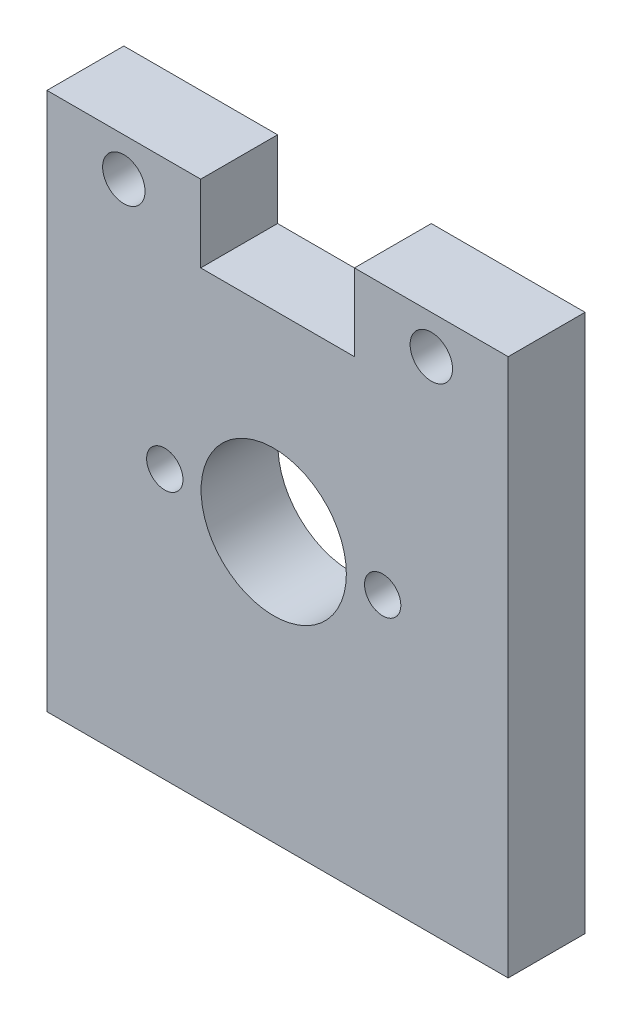
SolidWorks part; units mm, degrees
ref_plane "Front Plane" through (0, 0, 0) normal (0, 0, 1) x (1, 0, 0)
ref_plane "Top Plane" through (0, 0, 0) normal (0, 1, 0) x (1, 0, 0)
ref_plane "Right Plane" through (0, 0, 0) normal (1, 0, 0) x (0, 0, -1)
sketch "Sketch1" plane through (0, 0, 0) normal (0, 0, 1) x (1, 0, 0)
  line L1 (0, 0) -> (38.1, 0)
  line L2 (0, 0) -> (0, -44.45)
  line L3 (0, -44.45) -> (38.1, -44.45)
  line L4 (38.1, -44.45) -> (38.1, 0)
  dimension "D1" = 44.45
  dimension "D2" = 38.1
extrude "Boss-Extrude1" add sketch "Sketch1" along normal mid plane 6.35
sketch "Sketch2" [suppressed] plane through (0, 0, 3.175) normal (0, 0, 1) x (1, 0, 0)
  line L0 (6.2865, 0) -> (18.9865, 0)
  line L1 (6.2865, 0) -> (6.2865, -6.35)
  line L3 (18.9865, 0) -> (18.9865, -6.35)
  line L4 (76.2, -12.7) -> (76.2, 0) construction
  line L16 (76.2, 0) -> (0, 0) construction
  line L17 (14.1605, -13.97) -> (14.1605, -17.78)
  line L18 (16.4465, -13.97) -> (14.1605, -13.97)
  line L19 (16.4465, -11.43) -> (16.4465, -13.97)
  line L20 (14.1605, -11.43) -> (16.4465, -11.43)
  line L21 (11.1125, -13.97) -> (11.1125, -17.78)
  line L22 (8.8265, -13.97) -> (11.1125, -13.97)
  line L23 (8.8265, -11.43) -> (8.8265, -13.97)
  line L24 (11.1125, -11.43) -> (8.8265, -11.43)
  line L25 (11.1125, -6.35) -> (11.1125, -11.43)
  line L26 (14.1605, -17.78) -> (11.1125, -17.78)
  line L27 (14.1605, -6.35) -> (14.1605, -11.43)
  line L28 (14.1605, -6.35) -> (18.9865, -6.35)
  line L29 (6.2865, -6.35) -> (11.1125, -6.35)
  line L35 (12.6365, 0) -> (12.6365, -17.78) construction
  dimension "D1" = 12.7
  dimension "D2" = 6.35
  dimension "D3" = 11.43
  dimension "D4" = 13.97
  dimension "D5" = 17.78
  dimension "D6" = 3.048
  dimension "D7" = 3.048
  dimension "D8" = 7.62
  dimension "D9" = 3.81
  dimension "D10" = 1.524
  dimension "D11" = 65.0875
sketch "Sketch3" plane through (0, 0, 3.175) normal (0, 0, 1) x (1, 0, 0)
  line L1 (0, 0) -> (12.7, 0)
  line L2 (0, 0) -> (0, -12.7)
  line L3 (0, -12.7) -> (12.7, -12.7)
  line L4 (12.7, 0) -> (12.7, -12.7)
  dimension "D1" = 12.7
  dimension "D2" = 12.7
extrude "Cut-Extrude2" [suppressed] cut sketch "Sketch3" against normal up to next contours L3 L4 L1 L2
hole_wizard "#6 Clearance Hole1" positions "Sketch5" profile "Sketch4" hole size "#6" standard "ANSI Inch" end condition up to next
sketch "Sketch5" plane through (0, 0, 3.175) normal (0, 0, 1) x (1, 0, 0)
  line L0 (0, -3.175) -> (38.1, -3.175) construction
  line L1 (0, 0) -> (0, -44.45) construction
  line L2 (38.1, -44.45) -> (38.1, 0) construction
  line L4 (38.1, 0) -> (0, 0) construction
  point P0 (6.35, -3.175)
  point P13 (31.75, -3.175)
  dimension "D1" = 3.175
  dimension "D2" = 6.35
  dimension "D3" = 6.35
sketch "Sketch4" plane through (6.35, -3.175, 3.175) normal (1, 0, 0) x (0, -1, 0)
  line L0 (0, 0) -> (0, 6.35)
  line L1 (0, 6.35) -> (1.7526, 6.35)
  line L2 (1.7526, 6.35) -> (1.7526, 0)
  line L5 (1.7526, 0) -> (0, 0)
  line L11 (0, -6.35) -> (0, 107.95) construction
  dimension "Thru Hole Dia." = 3.5052
  dimension "Thru Hole Depth" = 6.35
sketch "Sketch6" plane through (0, 0, 3.175) normal (0, 0, 1) x (1, 0, 0)
  line L0 (19.05, 0) -> (19.05, -44.45) construction
  line L1 (38.1, 0) -> (0, 0) construction
  line L2 (0, -44.45) -> (38.1, -44.45) construction
  line L3 (25.4, -6.35) -> (12.7, -6.35)
  line L4 (25.4, -6.35) -> (25.4, 0)
  line L5 (12.7, -6.35) -> (12.7, 0)
  line L6 (25.4, 0) -> (12.7, 0)
  line L7 (25.4, -6.35) -> (12.7, 0) construction
  line L8 (12.7, -6.35) -> (25.4, 0) construction
  point P7 (19.05, -3.175)
  dimension "D1" = 12.7
  dimension "D2" = 6.35
extrude "Cut-Extrude3" cut sketch "Sketch6" against normal up to next
sketch "Sketch7" plane through (0, 0, 3.175) normal (0, 0, 1) x (1, 0, 0)
  line L0 (0, -44.45) -> (38.1, -44.45) construction
  line L1 (0, 0) -> (0, -44.45) construction
  circle A2 centre (18.7325, -22.225) radius 6
  dimension "D1" = 12
  dimension "D2" = 22.225
  dimension "D3" = 18.7325
extrude "Cut-Extrude4" cut sketch "Sketch7" against normal up to next
hole_wizard "M3 Clearance Hole1" positions "Sketch9" profile "Sketch8" hole size "M3" standard "ANSI Metric" end condition up to next
sketch "Sketch9" plane through (0, 0, 3.175) normal (0, 0, 1) x (1, 0, 0)
  line L16 (9.7325, -22.225) -> (27.7325, -22.225) construction
  circle A0 centre (18.7325, -22.225) radius 6 construction
  circle A1 centre (18.7325, -22.225) radius 6 construction
  point P54 (9.7325, -22.225)
  point P55 (27.7325, -22.225)
  dimension "D1" = 18
sketch "Sketch8" plane through (27.7325, -22.225, 3.175) normal (1, 0, 0) x (0, -1, 0)
  line L0 (0, 0) -> (0, 6.35)
  line L1 (0, 6.35) -> (1.5, 6.35)
  line L2 (1.5, 6.35) -> (1.5, 0)
  line L5 (1.5, 0) -> (0, 0)
  line L11 (0, -6.35) -> (0, 107.95) construction
  dimension "Thru Hole Dia." = 3
  dimension "Thru Hole Depth" = 6.35
ref_plane "Plane1" through (0, -3.175, 0) normal (0, 1, 0) x (1, 0, 0)
ref_plane "Plane2" through (19.05, 0, 0) normal (-1, 0, 0) x (0, 0, 1)
